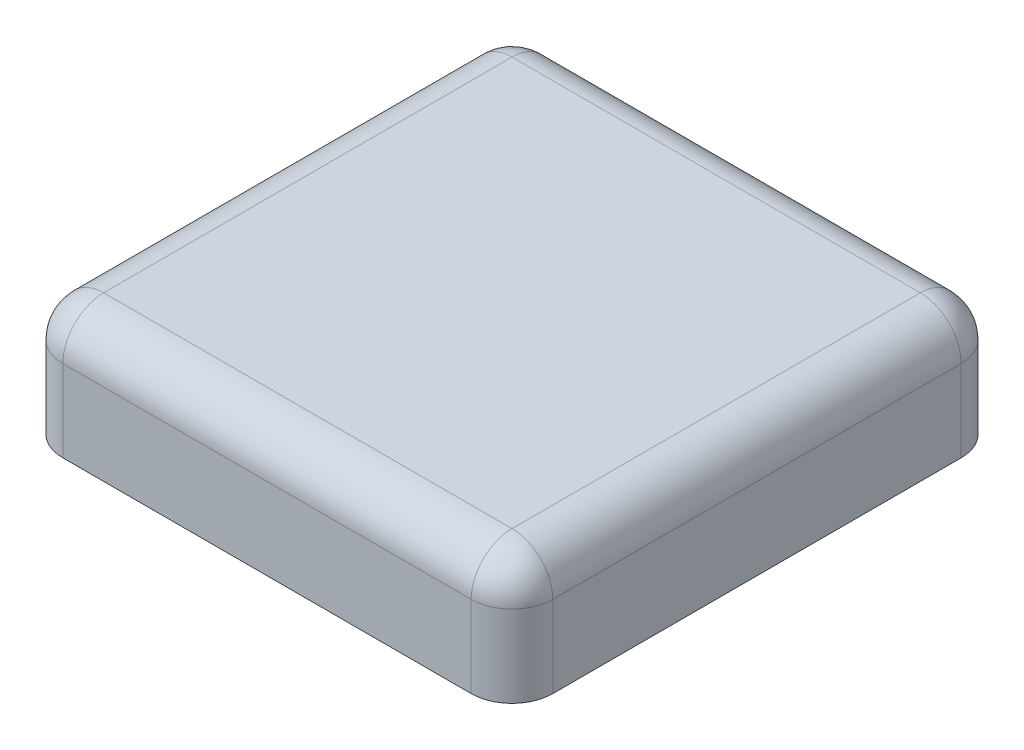
SolidWorks part; units mm, degrees
ref_plane "Front Plane" through (0, 0, 0) normal (0, 0, 1) x (1, 0, 0)
ref_plane "Top Plane" through (0, 0, 0) normal (0, 1, 0) x (1, 0, 0)
ref_plane "Right Plane" through (0, 0, 0) normal (1, 0, 0) x (0, 0, -1)
sketch "Sketch1" plane through (0, 0, 0) normal (0, 1, 0) x (1, 0, 0)
  line L1 (0, 0) -> (304.8, 0)
  line L2 (0, 0) -> (0, -304.8)
  line L3 (0, -304.8) -> (304.8, -304.8)
  line L4 (304.8, 0) -> (304.8, -304.8)
  dimension "D1" = 304.8
  dimension "D2" = 304.8
extrude "Boss-Extrude2" add sketch "Sketch1" along normal mid plane 76.2 contours L2 L3 L4 L1
fillet "Fillet1" radius 25.4 8 edges at (304.8, 38.1, 152.4) (152.4, 38.1, 304.8) (0, 38.1, 152.4) (152.4, 38.1, 0) (0, 0, 0) (304.8, 0, 0) (304.8, 0, 304.8) (0, 0, 304.8)
